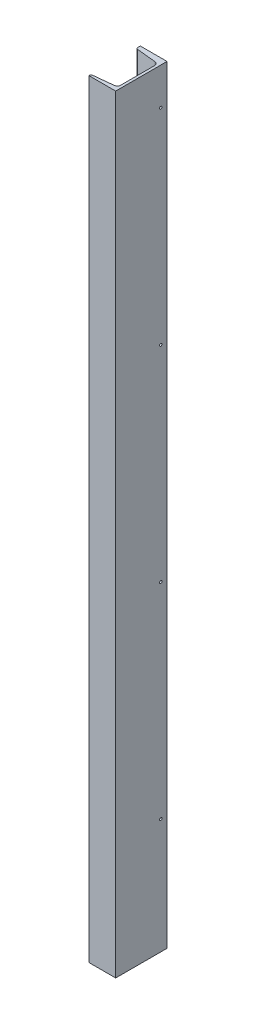
SolidWorks part; units mm, degrees
ref_plane "Front Plane" through (0, 0, 0) normal (0, 0, 1) x (1, 0, 0)
ref_plane "Top Plane" through (0, 0, 0) normal (0, 1, 0) x (1, 0, 0)
ref_plane "Right Plane" through (0, 0, 0) normal (1, 0, 0) x (0, 0, -1)
sketch "Sketch15" plane through (0, 0, 0) normal (0, 0, 1) x (1, 0, 0)
  line L0 (0, 0) -> (0, 1870)
  dimension "D1" = 1870
other "C channel 120 X 12(5)"
ref_plane "Plane5" through (0, 0, 0) normal (0, 1, 0) x (-1, 0, 0)
sketch "Sketch1" plane through (0, 0, 0) normal (0, 1, 0) x (-1, 0, 0)
  line L0 (65, 125) -> (0, 125)
  line L1 (65, 0) -> (0, 0)
  line L2 (0, 125) -> (0, 0)
  line L6 (65, 125) -> (65, 124.1647)
  line L7 (65, 0) -> (65, 5.8453)
  line L12 (6.3, 106.74) -> (6.3, 23.27)
  line L17 (13.4638, 114.6962) -> (60.9704, 119.6893)
  line L18 (13.4638, 15.3138) -> (60.9704, 10.3207)
  arc A0 (60.9704, 119.6893) -> (65, 124.1647) centre (60.5, 124.1647) ccw
  arc A1 (60.9704, 10.3207) -> (65, 5.8453) centre (60.5, 5.8453) cw
  arc A9 (6.3, 23.27) -> (13.4638, 15.3138) centre (14.3, 23.27) ccw
  arc A10 (6.3, 106.74) -> (13.4638, 114.6962) centre (14.3, 106.74) cw
  point P8 (0, 62.5)
  point P9 (6.3, 65.005)
  point P10 (32.5, 125)
  point P11 (32.5, 0)
  point P12 (65, 9.8971)
  point P13 (65, 120.1129)
  point P14 (0, 0)
  dimension "D4" = 4.5
  dimension "RI" = 8
  dimension "D2" = 6
  dimension "D3" = 18.26
  dimension "Depth" = 125
  dimension "BF" = 65
  dimension "TW" = 6.3
  dimension "d1" = 83.47
sketch "Sketch16" plane through (0, 0, 0) normal (1, 0, 0) x (0, 0, -1)
  circle A0 centre (-15.2, 280) radius 3 construction
  circle A1 centre (-15.2, 780) radius 3 construction
  circle A2 centre (-15.2, 1280) radius 3 construction
  circle A3 centre (-15.2, 1780) radius 3 construction
  circle A4 centre (-15.2, 280) radius 3
  circle A5 centre (-15.2, 780) radius 3
  circle A6 centre (-15.2, 1280) radius 3
  circle A7 centre (-15.2, 1780) radius 3
extrude "Cut-Extrude1" cut sketch "Sketch16" against normal through all
sketch "Sketch17" [suppressed] plane through (0, 0, 0) normal (1, 0, 0) x (0, 0, -1)
  circle A0 centre (-15.2, 1280) radius 3 construction
  circle A1 centre (-109.8, 1280) radius 3 construction
  circle A2 centre (-15.2, 1780) radius 3 construction
  circle A3 centre (-109.8, 1780) radius 3 construction
  circle A4 centre (-15.2, 1280) radius 3
  circle A5 centre (-109.8, 1280) radius 3
  circle A6 centre (-15.2, 1780) radius 3
  circle A7 centre (-109.8, 1780) radius 3
  circle A8 centre (-109.8, 280) radius 3 construction
  circle A9 centre (-15.2, 280) radius 3 construction
  circle A10 centre (-15.2, 780) radius 3 construction
  circle A11 centre (-109.8, 780) radius 3 construction
  circle A12 centre (-109.8, 280) radius 3
  circle A13 centre (-15.2, 280) radius 3
  circle A14 centre (-15.2, 780) radius 3
  circle A15 centre (-109.8, 780) radius 3
extrude "Cut-Extrude2" [suppressed] cut sketch "Sketch17" against normal through all
sketch "Sketch18" [suppressed] plane through (0, 0, 0) normal (1, 0, 0) x (0, 0, -1)
  circle A0 centre (-109.8, 280) radius 3 construction
  circle A1 centre (-109.8, 780) radius 3 construction
  circle A2 centre (-109.8, 1280) radius 3 construction
  circle A3 centre (-109.8, 280) radius 3
  circle A4 centre (-109.8, 780) radius 3
  circle A5 centre (-109.8, 1280) radius 3
  circle A6 centre (-109.8, 1780) radius 3 construction
  circle A7 centre (-109.8, 1780) radius 3
extrude "Cut-Extrude3" [suppressed] cut sketch "Sketch18" against normal through all
sketch "Sketch19" [suppressed] plane through (2, 0, 0) normal (1, 0, 0) x (0, 0, -1)
  circle A0 centre (-110, 245) radius 4 construction
  circle A1 centre (-110, 880) radius 4 construction
  circle A2 centre (-110, 1515) radius 4 construction
  circle A3 centre (-110, 245) radius 4
  circle A4 centre (-110, 880) radius 4
  circle A5 centre (-110, 1515) radius 4
extrude "Cut-Extrude4" [suppressed] cut sketch "Sketch19" against normal through all
